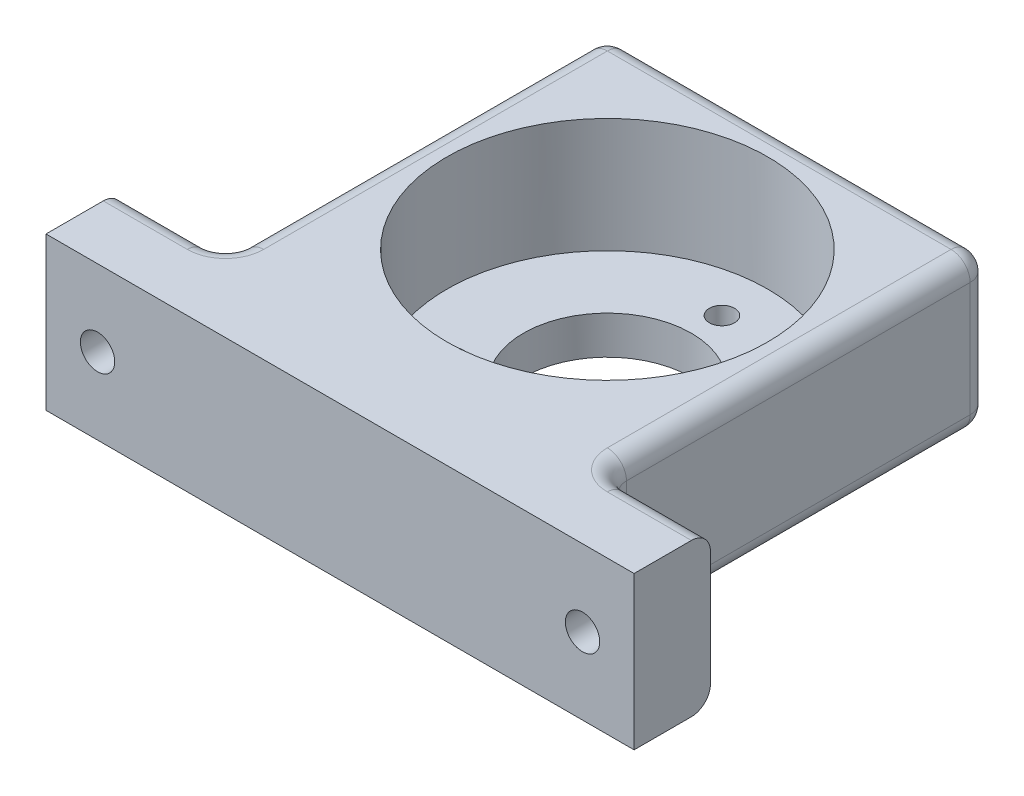
SolidWorks part; units mm, degrees
ref_plane "Front Plane" through (0, 0, 0) normal (0, 0, 1) x (1, 0, 0)
ref_plane "Top Plane" through (0, 0, 0) normal (0, 1, 0) x (1, 0, 0)
ref_plane "Right Plane" through (0, 0, 0) normal (1, 0, 0) x (0, 0, -1)
sketch "Sketch1" plane through (0, 0, 0) normal (0, 1, 0) x (1, 0, 0)
  line L1 (-25, -25) -> (-38.5, -25)
  line L2 (-38.5, -25) -> (-38.5, -35)
  line L3 (-38.5, -35) -> (38.5, -35)
  line L4 (38.5, -35) -> (38.5, -25)
  line L5 (38.5, -25) -> (25, -25)
  line L7 (-25, -25) -> (-25, 25)
  line L8 (-25, 25) -> (25, 25)
  line L9 (25, 25) -> (25, -25)
  circle A1 centre (0, 0) radius 11
  point P11 (0, 25)
  point P12 (25, 0)
  dimension "D1" = 50
  dimension "D2" = 22
  dimension "D3" = 50
  dimension "D5" = 77
  dimension "D6" = 10
extrude "Boss-Extrude1" add sketch "Sketch1" along normal blind 20
sketch "Sketch2" plane through (0, 20, 0) normal (0, 1, 0) x (1, 0, 0)
  circle A0 centre (0, 0) radius 21
  dimension "D1" = 42
extrude "Cut-Extrude1" cut sketch "Sketch2" against normal offset from surface (15 mm away) 5 up to face at (0, 0, 15)
sketch "Sketch3" plane through (0, 0, 25) normal (0, 0, -1) x (-1, 0, 0)
  line L0 (-38.5, 20) -> (-25, 20) construction
  line L1 (-38.5, 20) -> (-38.5, 0) construction
  line L4 (0, 11) -> (0, -11) construction
  point P0 (-31.75, 10)
  point P4 (-31.75, 20)
  point P7 (-38.5, 10)
  point P8 (0, 0)
  point P9 (0, 0)
  point P10 (0, 0)
  point P13 (31.75, 10)
hole_wizard "CBORE for M4 Hex Socket Head Cap Screw2" positions "3DSketch2" profile "Sketch6" counterbore size "M4" standard "DIN" end condition up to next
sketch3d "3DSketch2"
  point P0 (31.75, 10, 25)
  point P3 (-31.75, 10, 25)
sketch "Sketch6" plane through (31.75, 10, 25) normal (1, 0, 0) x (0, 1, 0)
  line L0 (0, 0) -> (0, 10)
  line L1 (0, 10) -> (2.25, 10)
  line L3 (2.25, 10) -> (2.25, 4.4)
  line L4 (2.25, 4.4) -> (4, 4.4)
  line L5 (4, 4.4) -> (4, 0)
  line L7 (4, 0) -> (0, 0)
  line L11 (0, -6.35) -> (0, 107.95) construction
  dimension "Thru Hole Dia." = 4.5
  dimension "Thru Hole Depth" = 10
  dimension "C'Bore Dia." = 8
  dimension "C'Bore Depth" = 4.4
sketch "Sketch5" plane through (0, 0, 0) normal (0, -1, 0) x (1, 0, 0)
  line L0 (0, 0) -> (0, -32.1124) construction
  circle A0 centre (12.9904, 7.5) radius 1.65
  circle A1 centre (-12.9904, 7.5) radius 1.65
  circle A2 centre (0, -15) radius 1.65
  circle A3 centre (0, 0) radius 15 construction
  dimension "D1" = 3.3
  dimension "D2" = 30
  dimension "D3" = 120
  dimension "D4" = 240
extrude "Cut-Extrude2" cut sketch "Sketch5" against normal up to next
fillet "Fillet1" radius 2.5 14 edges at (25, 20, 0) (25, 0, 0) (-25, 0, 0) (-25, 20, 0) (25, 10, -25) (-25, 10, -25) (31.75, 20, 25) (31.75, 0, 25) (-31.75, 20, 25) (-31.75, 0, 25) (25, 10, 25) (-25, 10, 25) (0, 20, -25) (0, 0, -25)
